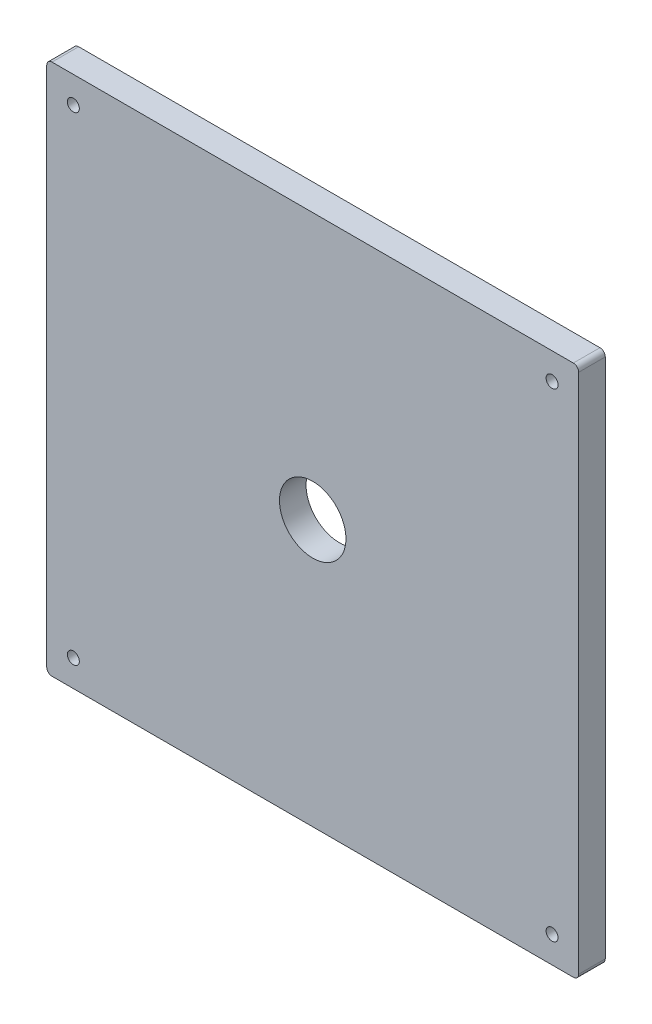
SolidWorks part; units mm, degrees
ref_plane "Plan de face" through (0, 0, 0) normal (0, 0, 1) x (1, 0, 0)
ref_plane "Plan de dessus" through (0, 0, 0) normal (0, 1, 0) x (1, 0, 0)
ref_plane "Plan de droite" through (0, 0, 0) normal (1, 0, 0) x (0, 0, -1)
sketch "Esquisse1" plane through (0, 0, 0) normal (0, 0, 1) x (1, 0, 0)
  line L1 (-98, -100) -> (98, -100)
  line L2 (-100, -98) -> (-100, 98)
  line L3 (-98, 100) -> (98, 100)
  line L4 (100, -98) -> (100, 98)
  line L5 (-100, -100) -> (100, 100) construction
  line L6 (-100, 100) -> (100, -100) construction
  arc A0 (-98, -100) -> (-100, -98) centre (-98, -98) cw
  arc A1 (98, -100) -> (100, -98) centre (98, -98) ccw
  arc A2 (100, 98) -> (98, 100) centre (98, 98) ccw
  arc A3 (-98, 100) -> (-100, 98) centre (-98, 98) ccw
  circle A4 centre (0, 0) radius 12.5
  point P0 (0, 0)
  dimension "D3" = 2
  dimension "D4" = 25
  dimension "D1" = 200
  dimension "D2" = 200
extrude "Boss.-Extru.1" add sketch "Esquisse1" along normal blind 10
hole_wizard "Dégagement M41" positions "Esquisse5" profile "Esquisse4" hole size "M4" standard "JIS" end condition through all
sketch "Esquisse5" plane through (0, 0, 10) normal (0, 0, 1) x (1, 0, 0)
  point P0 (-90, 90)
  point P2 (-90, -90)
  point P4 (90, -90)
  point P6 (90, 90)
sketch "Esquisse4" plane through (-90, 90, 10) normal (1, 0, 0) x (0, -1, 0)
  line L0 (0, 0) -> (0, 10)
  line L1 (0, 10) -> (2.25, 10)
  line L2 (2.25, 10) -> (2.25, 0)
  line L5 (2.25, 0) -> (0, 0)
  line L11 (0, -6.35) -> (0, 107.95) construction
  dimension "Diamètre du perçage jusqu'au prochain" = 4.5
  dimension "Profondeur du perçage jusqu'au prochain" = 10
hole_wizard "Chambrage pour vis à tête ronde bombée M41" positions "Esquisse7" profile "Esquisse6" counterbore size "M4" standard "Ansi Metric" end condition through all
sketch "Esquisse7" plane through (0, 0, 0) normal (0, 0, -1) x (-1, 0, 0)
  point P0 (-90, 90)
  point P2 (90, 90)
  point P4 (90, -90)
  point P6 (-90, -90)
sketch "Esquisse6" plane through (90, 90, 0) normal (1, 0, 0) x (0, 1, 0)
  line L0 (0, 0) -> (0, 10)
  line L1 (0, 10) -> (2.25, 10)
  line L2 (2.25, 3.125) -> (2.25, 10)
  line L3 (2.25, 3.125) -> (2.275, 3.1)
  line L4 (2.275, 3.1) -> (4.5, 3.1)
  line L5 (4.5, 3.1) -> (4.5, 0)
  line L7 (0, 0) -> (4.5, 0)
  line L9 (-2.25, 3.125) -> (-2.275, 3.1) construction
  line L11 (0, -6.35) -> (0, 107.95) construction
  dimension "Diamètre du perçage jusqu'au prochain" = 4.5
  dimension "Profondeur du perçage jusqu'au prochain" = 10
  dimension "Diamètre du chambrage" = 9
  dimension "Profondeur du chambrage" = 3.1
  dimension "Diamètre du fraisage milieu" = 4.55
  dimension "Angle du fraisage milieu" = 90
